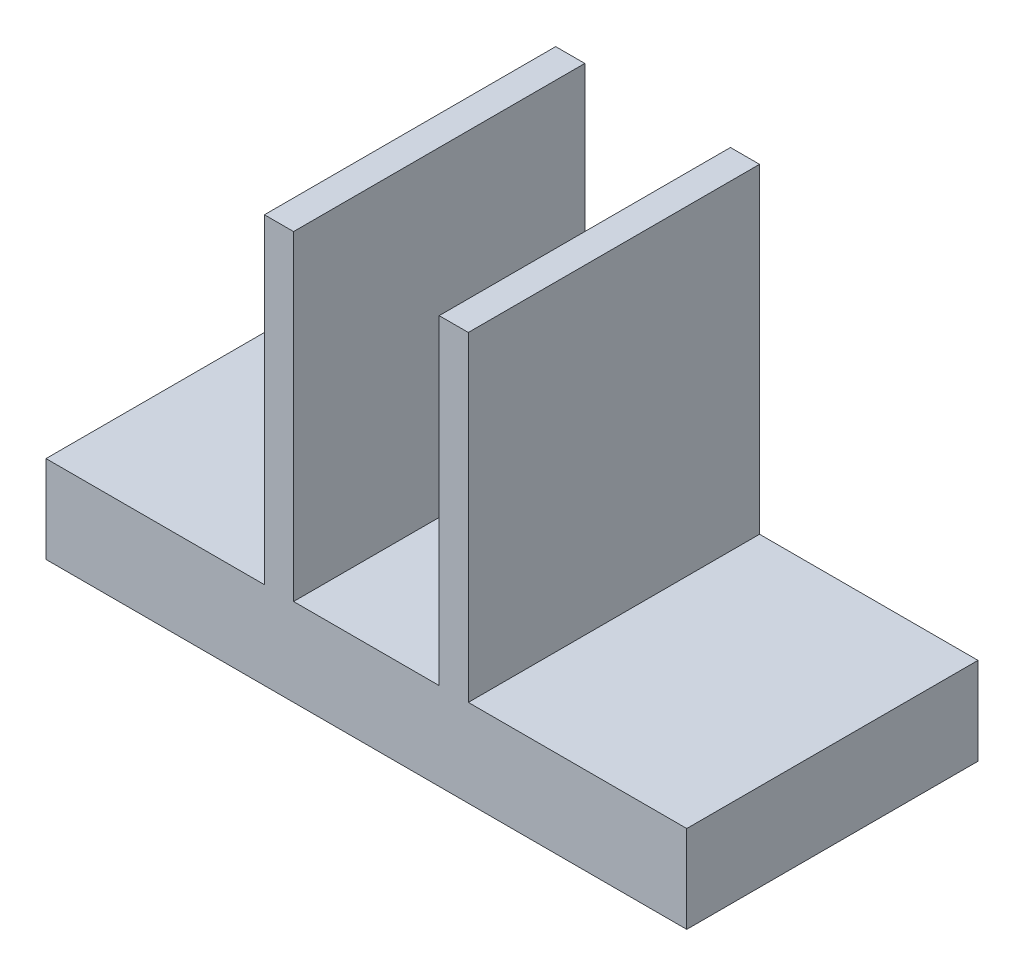
SolidWorks part; units mm, degrees
ref_plane "Спереди" through (0, 0, 0) normal (0, 0, 1) x (1, 0, 0)
ref_plane "Сверху" through (0, 0, 0) normal (0, 1, 0) x (1, 0, 0)
ref_plane "Справа" through (0, 0, 0) normal (1, 0, 0) x (0, 0, -1)
sketch "Эскиз1" plane through (0, 0, 0) normal (0, 0, 1) x (1, 0, 0)
  line L0 (0, 0) -> (22, 0)
  line L1 (22, 0) -> (22, 3)
  line L2 (0, 0) -> (0, 3)
  line L3 (0, 3) -> (7.5, 3)
  line L4 (22, 3) -> (14.5, 3)
  line L5 (7.5, 3) -> (7.5, 14)
  line L6 (8.5, 3) -> (13.5, 3)
  line L7 (7.5, 14) -> (8.5, 14)
  line L8 (8.5, 14) -> (8.5, 3)
  line L9 (14.5, 3) -> (14.5, 14)
  line L10 (14.5, 14) -> (13.5, 14)
  line L11 (13.5, 14) -> (13.5, 3)
extrude "Бобышка-Вытянуть1" add sketch "Эскиз1" along normal blind 10
ref_plane "Плоскость1" through (14, 0, 0) normal (1, 0, 0) x (0, 0, -1)
